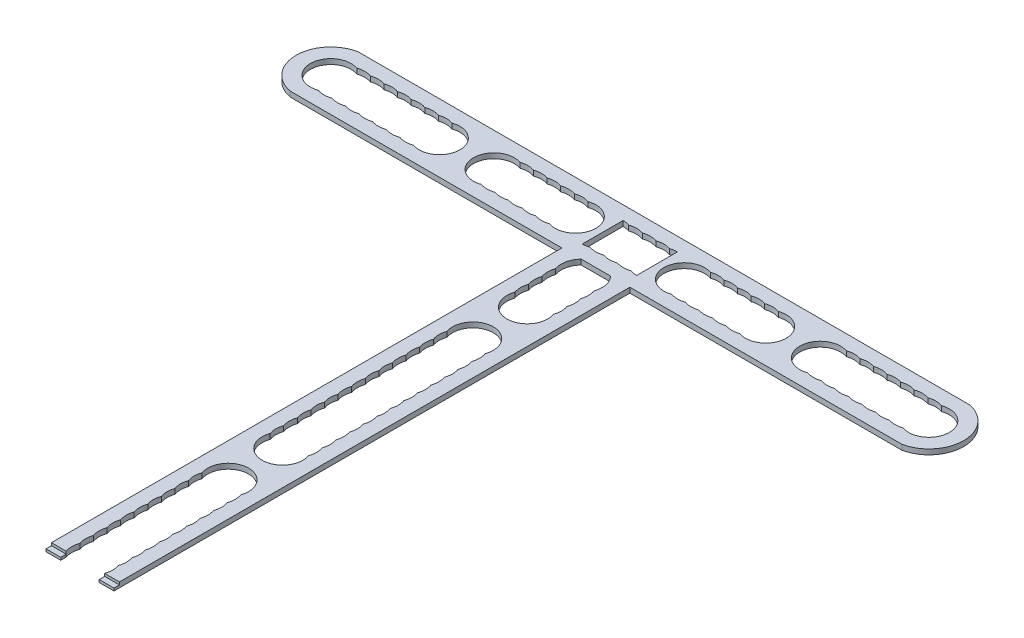
SolidWorks part; units mm, degrees
ref_plane "Front Plane" through (0, 0, 0) normal (0, 0, 1) x (1, 0, 0)
ref_plane "Top Plane" through (0, 0, 0) normal (0, 1, 0) x (1, 0, 0)
ref_plane "Right Plane" through (0, 0, 0) normal (1, 0, 0) x (0, 0, -1)
sketch "Sketch3" plane through (0, 0, 0) normal (0, 1, 0) x (1, 0, 0)
  line L0 (-112.5, 0) -> (112.5, 0) construction
  line L1 (-112.5, -12.5) -> (112.5, -12.5)
  line L2 (-112.5, -12.5) -> (-112.5, 12.5) construction
  line L3 (-112.5, 12.5) -> (112.5, 12.5)
  line L4 (112.5, -12.5) -> (112.5, 12.5) construction
  line L5 (-112.5, -12.5) -> (112.5, 12.5) construction
  line L6 (-112.5, 12.5) -> (112.5, -12.5) construction
  line L7 (60, 12.5) -> (60, -12.5) construction
  line L8 (10, 7.5) -> (10, -7.5)
  line L9 (0, 12.5) -> (0, -12.5) construction
  line L10 (0, 12.5) -> (0, -12.5)
  arc A0 (-2.5, 7.0711) -> (2.5, 7.0711) centre (0, 0) cw
  arc A1 (2.5, 7.0711) -> (7.5, 7.0711) centre (5, 0) cw
  arc A2 (7.5, 7.0711) -> (12.5, 7.0711) centre (10, 0) cw
  arc A3 (12.5, 7.0711) -> (17.5, 7.0711) centre (15, 0) cw
  arc A4 (17.5, 7.0711) -> (22.5, 7.0711) centre (20, 0) cw
  arc A5 (22.5, 7.0711) -> (27.5, 7.0711) centre (25, 0) cw
  arc A6 (27.5, 7.0711) -> (32.5, 7.0711) centre (30, 0) cw
  arc A7 (32.5, 7.0711) -> (37.5, 7.0711) centre (35, 0) cw
  arc A8 (37.5, 7.0711) -> (42.5, 7.0711) centre (40, 0) cw
  arc A9 (42.5, 7.0711) -> (47.5, 7.0711) centre (45, 0) cw
  arc A10 (47.5, 7.0711) -> (52.5, 7.0711) centre (50, 0) cw
  arc A11 (52.5, 7.0711) -> (57.5, 7.0711) centre (55, 0) cw
  arc A12 (57.5, 7.0711) -> (62.5, 7.0711) centre (60, 0) cw
  arc A13 (62.5, 7.0711) -> (67.5, 7.0711) centre (65, 0) cw
  arc A14 (67.5, 7.0711) -> (72.5, 7.0711) centre (70, 0) cw
  arc A15 (72.5, 7.0711) -> (77.5, 7.0711) centre (75, 0) cw
  arc A16 (77.5, 7.0711) -> (82.5, 7.0711) centre (80, 0) cw
  arc A17 (82.5, 7.0711) -> (87.5, 7.0711) centre (85, 0) cw
  arc A18 (87.5, 7.0711) -> (92.5, 7.0711) centre (90, 0) cw
  arc A19 (92.5, 7.0711) -> (97.5, 7.0711) centre (95, 0) cw
  arc A20 (97.5, 7.0711) -> (102.5, 7.0711) centre (100, 0) cw
  arc A21 (102.5, 7.0711) -> (107.5, 7.0711) centre (105, 0) cw
  arc A22 (107.5, 7.0711) -> (112.5, 7.0711) centre (110, 0) cw
  arc A23 (107.5, -7.0711) -> (112.5, -7.0711) centre (110, 0) ccw
  arc A24 (102.5, -7.0711) -> (107.5, -7.0711) centre (105, 0) ccw
  arc A25 (97.5, -7.0711) -> (102.5, -7.0711) centre (100, 0) ccw
  arc A26 (92.5, -7.0711) -> (97.5, -7.0711) centre (95, 0) ccw
  arc A27 (87.5, -7.0711) -> (92.5, -7.0711) centre (90, 0) ccw
  arc A28 (82.5, -7.0711) -> (87.5, -7.0711) centre (85, 0) ccw
  arc A29 (77.5, -7.0711) -> (82.5, -7.0711) centre (80, 0) ccw
  arc A30 (72.5, -7.0711) -> (77.5, -7.0711) centre (75, 0) ccw
  arc A31 (67.5, -7.0711) -> (72.5, -7.0711) centre (70, 0) ccw
  arc A32 (62.5, -7.0711) -> (67.5, -7.0711) centre (65, 0) ccw
  arc A33 (57.5, -7.0711) -> (62.5, -7.0711) centre (60, 0) ccw
  arc A34 (52.5, -7.0711) -> (57.5, -7.0711) centre (55, 0) ccw
  arc A35 (47.5, -7.0711) -> (52.5, -7.0711) centre (50, 0) ccw
  arc A36 (42.5, -7.0711) -> (47.5, -7.0711) centre (45, 0) ccw
  arc A37 (37.5, -7.0711) -> (42.5, -7.0711) centre (40, 0) ccw
  arc A38 (32.5, -7.0711) -> (37.5, -7.0711) centre (35, 0) ccw
  arc A39 (27.5, -7.0711) -> (32.5, -7.0711) centre (30, 0) ccw
  arc A40 (22.5, -7.0711) -> (27.5, -7.0711) centre (25, 0) ccw
  arc A41 (17.5, -7.0711) -> (22.5, -7.0711) centre (20, 0) ccw
  arc A42 (12.5, -7.0711) -> (17.5, -7.0711) centre (15, 0) ccw
  arc A43 (7.5, -7.0711) -> (12.5, -7.0711) centre (10, 0) ccw
  arc A44 (2.5, -7.0711) -> (7.5, -7.0711) centre (5, 0) ccw
  arc A45 (-2.5, -7.0711) -> (2.5, -7.0711) centre (0, 0) ccw
  arc A46 (112.5, 7.0711) -> (112.5, -7.0711) centre (110, 0) cw
  arc A47 (112.5, 12.5) -> (112.5, -12.5) centre (110, 0) cw
  arc A48 (52.5, 7.0711) -> (52.5, -7.0711) centre (50, 0) cw
  arc A49 (67.5, 7.0711) -> (67.5, -7.0711) centre (70, 0) ccw
  arc A50 (17.5, 7.0711) -> (17.5412, -7.0855) centre (20, 0) ccw
  point P0 (0, 0)
  dimension "D4" = 7.5
  dimension "D1" = 225
  dimension "D2" = 25
  dimension "D3" = 5
  dimension "D6" = 60
  dimension "D5" = 23
extrude "Boss-Extrude1" add sketch "Sketch3" along normal blind 1.9 contours A47 L3 L10 A0 A1 A2 A3 A4 A5 A6 A7 A8 A9 A10 A11 A12 A13 A14 A15 A16 A17 A18 A19 A20 A21 A22 A46 A23 A24 A25 A26 A27 A28 A29 A30 A31 A32 A33 A34 A35 A36 A37 A38 A39 A40 A41 A42 A43 | A50 A3 A2 L8 A43 A42 | A49 A13 A12 A11 A48 A34 A33 A32
mirror "Mirror1" about plane through (0, 0, 0) normal (1, 0, 0) of "Boss-Extrude1"
sketch "Sketch4" plane through (0, 0, 0) normal (0, 1, 0) x (1, 0, 0)
  line L0 (-112.5, -12.5) -> (112.5, -12.5) construction
  line L1 (-12.5, -382.9289) -> (12.5, -382.9289)
  line L2 (-12.5, -382.9289) -> (-12.5, -12.5)
  line L3 (-12.5, -12.5) -> (12.5, -12.5)
  line L4 (12.5, -382.9289) -> (12.5, -12.5)
  line L5 (-12.5, -382.9289) -> (12.5, -12.5) construction
  line L6 (-12.5, -12.5) -> (12.5, -382.9289) construction
  line L7 (0, 0) -> (0, -382.9289) construction
  line L8 (-12.5, -200.2145) -> (12.5, -200.2145)
  line L9 (-12.5, -46.875) -> (12.5, -46.875) construction
  line L10 (-12.5, -140.625) -> (12.5, -140.625) construction
  arc A0 (7.0711, -195.2145) -> (7.0711, -200.2145) centre (0, -197.7145) cw
  arc A1 (7.0711, -190.2145) -> (7.0711, -195.2145) centre (0, -192.7145) cw
  arc A2 (7.0711, -185.2145) -> (7.0711, -190.2145) centre (0, -187.7145) cw
  arc A3 (7.0711, -180.2145) -> (7.0711, -185.2145) centre (0, -182.7145) cw
  arc A4 (7.0711, -175.2145) -> (7.0711, -180.2145) centre (0, -177.7145) cw
  arc A5 (7.0711, -170.2145) -> (7.0711, -175.2145) centre (0, -172.7145) cw
  arc A6 (7.0711, -165.2145) -> (7.0711, -170.2145) centre (0, -167.7145) cw
  arc A7 (7.0711, -160.2145) -> (7.0711, -165.2145) centre (0, -162.7145) cw
  arc A8 (7.0711, -155.2145) -> (7.0711, -160.2145) centre (0, -157.7145) cw
  arc A9 (7.0711, -150.2145) -> (7.0711, -155.2145) centre (0, -152.7145) cw
  arc A10 (7.0711, -145.2145) -> (7.0711, -150.2145) centre (0, -147.7145) cw
  arc A11 (7.0711, -140.2145) -> (7.0711, -145.2145) centre (0, -142.7145) cw
  arc A12 (7.0711, -135.2145) -> (7.0711, -140.2145) centre (0, -137.7145) cw
  arc A13 (7.0711, -130.2145) -> (7.0711, -135.2145) centre (0, -132.7145) cw
  arc A14 (7.0711, -125.2145) -> (7.0711, -130.2145) centre (0, -127.7145) cw
  arc A15 (7.0711, -120.2145) -> (7.0711, -125.2145) centre (0, -122.7145) cw
  arc A16 (7.0711, -115.2145) -> (7.0711, -120.2145) centre (0, -117.7145) cw
  arc A17 (7.0711, -110.2145) -> (7.0711, -115.2145) centre (0, -112.7145) cw
  arc A18 (7.0711, -105.2145) -> (7.0711, -110.2145) centre (0, -107.7145) cw
  arc A19 (7.0711, -100.2145) -> (7.0711, -105.2145) centre (0, -102.7145) cw
  arc A20 (7.0711, -95.2145) -> (7.0711, -100.2145) centre (0, -97.7145) cw
  arc A21 (7.0711, -90.2145) -> (7.0711, -95.2145) centre (0, -92.7145) cw
  arc A22 (7.0711, -85.2145) -> (7.0711, -90.2145) centre (0, -87.7145) cw
  arc A23 (7.0711, -80.2145) -> (7.0711, -85.2145) centre (0, -82.7145) cw
  arc A24 (7.0711, -75.2145) -> (7.0711, -80.2145) centre (0, -77.7145) cw
  arc A25 (7.0711, -70.2145) -> (7.0711, -75.2145) centre (0, -72.7145) cw
  arc A26 (7.0711, -65.2145) -> (7.0711, -70.2145) centre (0, -67.7145) cw
  arc A27 (7.0711, -60.2145) -> (7.0711, -65.2145) centre (0, -62.7145) cw
  arc A28 (7.0711, -55.2145) -> (7.0711, -60.2145) centre (0, -57.7145) cw
  arc A29 (7.0711, -50.2145) -> (7.0711, -55.2145) centre (0, -52.7145) cw
  arc A30 (7.0711, -45.2145) -> (7.0711, -50.2145) centre (0, -47.7145) cw
  arc A31 (7.0711, -40.2145) -> (7.0711, -45.2145) centre (0, -42.7145) cw
  arc A32 (7.0711, -35.2145) -> (7.0711, -40.2145) centre (0, -37.7145) cw
  arc A33 (7.0711, -30.2145) -> (7.0711, -35.2145) centre (0, -32.7145) cw
  arc A34 (7.0711, -25.2145) -> (7.0711, -30.2145) centre (0, -27.7145) cw
  arc A35 (7.0711, -20.2145) -> (7.0711, -25.2145) centre (0, -22.7145) cw
  arc A36 (7.0711, -15.2145) -> (7.0711, -20.2145) centre (0, -17.7145) cw
  arc A37 (-7.0711, -195.2145) -> (-7.0711, -200.2145) centre (0, -197.7145) ccw
  arc A38 (-7.0711, -190.2145) -> (-7.0711, -195.2145) centre (0, -192.7145) ccw
  arc A39 (-7.0711, -185.2145) -> (-7.0711, -190.2145) centre (0, -187.7145) ccw
  arc A40 (-7.0711, -180.2145) -> (-7.0711, -185.2145) centre (0, -182.7145) ccw
  arc A41 (-7.0711, -175.2145) -> (-7.0711, -180.2145) centre (0, -177.7145) ccw
  arc A42 (-7.0711, -170.2145) -> (-7.0711, -175.2145) centre (0, -172.7145) ccw
  arc A43 (-7.0711, -165.2145) -> (-7.0711, -170.2145) centre (0, -167.7145) ccw
  arc A44 (-7.0711, -160.2145) -> (-7.0711, -165.2145) centre (0, -162.7145) ccw
  arc A45 (-7.0711, -155.2145) -> (-7.0711, -160.2145) centre (0, -157.7145) ccw
  arc A46 (-7.0711, -150.2145) -> (-7.0711, -155.2145) centre (0, -152.7145) ccw
  arc A47 (-7.0711, -145.2145) -> (-7.0711, -150.2145) centre (0, -147.7145) ccw
  arc A48 (-7.0711, -140.2145) -> (-7.0711, -145.2145) centre (0, -142.7145) ccw
  arc A49 (-7.0711, -135.2145) -> (-7.0711, -140.2145) centre (0, -137.7145) ccw
  arc A50 (-7.0711, -130.2145) -> (-7.0711, -135.2145) centre (0, -132.7145) ccw
  arc A51 (-7.0711, -125.2145) -> (-7.0711, -130.2145) centre (0, -127.7145) ccw
  arc A52 (-7.0711, -120.2145) -> (-7.0711, -125.2145) centre (0, -122.7145) ccw
  arc A53 (-7.0711, -115.2145) -> (-7.0711, -120.2145) centre (0, -117.7145) ccw
  arc A54 (-7.0711, -110.2145) -> (-7.0711, -115.2145) centre (0, -112.7145) ccw
  arc A55 (-7.0711, -105.2145) -> (-7.0711, -110.2145) centre (0, -107.7145) ccw
  arc A56 (-7.0711, -100.2145) -> (-7.0711, -105.2145) centre (0, -102.7145) ccw
  arc A57 (-7.0711, -95.2145) -> (-7.0711, -100.2145) centre (0, -97.7145) ccw
  arc A58 (-7.0711, -90.2145) -> (-7.0711, -95.2145) centre (0, -92.7145) ccw
  arc A59 (-7.0711, -85.2145) -> (-7.0711, -90.2145) centre (0, -87.7145) ccw
  arc A60 (-7.0711, -80.2145) -> (-7.0711, -85.2145) centre (0, -82.7145) ccw
  arc A61 (-7.0711, -75.2145) -> (-7.0711, -80.2145) centre (0, -77.7145) ccw
  arc A62 (-7.0711, -70.2145) -> (-7.0711, -75.2145) centre (0, -72.7145) ccw
  arc A63 (-7.0711, -65.2145) -> (-7.0711, -70.2145) centre (0, -67.7145) ccw
  arc A64 (-7.0711, -60.2145) -> (-7.0711, -65.2145) centre (0, -62.7145) ccw
  arc A65 (-7.0711, -55.2145) -> (-7.0711, -60.2145) centre (0, -57.7145) ccw
  arc A66 (-7.0711, -50.2145) -> (-7.0711, -55.2145) centre (0, -52.7145) ccw
  arc A67 (-7.0711, -45.2145) -> (-7.0711, -50.2145) centre (0, -47.7145) ccw
  arc A68 (-7.0711, -40.2145) -> (-7.0711, -45.2145) centre (0, -42.7145) ccw
  arc A69 (-7.0711, -35.2145) -> (-7.0711, -40.2145) centre (0, -37.7145) ccw
  arc A70 (-7.0711, -30.2145) -> (-7.0711, -35.2145) centre (0, -32.7145) ccw
  arc A71 (-7.0711, -25.2145) -> (-7.0711, -30.2145) centre (0, -27.7145) ccw
  arc A72 (-7.0711, -20.2145) -> (-7.0711, -25.2145) centre (0, -22.7145) ccw
  arc A73 (-7.0711, -15.2145) -> (-7.0711, -20.2145) centre (0, -17.7145) ccw
  arc A74 (7.0711, -15.2145) -> (-7.0711, -15.2145) centre (0, -17.7145) ccw
  arc A75 (-7.0711, -40.2145) -> (7.0711, -40.2145) centre (0, -37.7145) ccw
  arc A76 (7.0711, -55.2145) -> (-7.0711, -55.2145) centre (0, -57.7145) ccw
  arc A77 (-7.0711, -130.2145) -> (7.0711, -130.2145) centre (0, -127.7145) ccw
  arc A78 (7.0711, -145.2145) -> (-7.0711, -145.2145) centre (0, -147.7145) ccw
  point P0 (0, -197.7145)
  dimension "D4" = 7.5
  dimension "D3" = 5
  dimension "D1" = 25
  dimension "D2" = 390
  dimension "D6" = 46.875
  dimension "D7" = 93.75
  dimension "D5" = 37
extrude "Boss-Extrude2" add sketch "Sketch4" along normal blind 1.9 contours A74 A36 A35 A34 A33 A32 A31 A30 A29 A28 A27 A26 A25 A24 A23 A22 A21 A20 A19 A18 A17 A16 A15 A14 A13 A12 A11 A10 A9 A8 A7 A6 A5 A4 A3 A2 A1 A0 L8 L4 L3 | A74 L3 L2 L8 A37 A38 A39 A40 A41 A42 A43 A44 A45 A46 A47 A48 A49 A50 A51 A52 A53 A54 A55 A56 A57 A58 A59 A60 A61 A62 A63 A64 A65 A66 A67 A68 A69 A70 A71 A72 A73 | A76 A29 A30 A31 A75 A68 A67 A66 | A78 A11 A12 A13 A77 A50 A49 A48
sketch "Sketch5" plane through (0, 0, 0) normal (0, 1, 0) x (1, 0, 0)
  line L0 (7.0711, -200.2145) -> (12.5, -200.2145) construction
  line L1 (-12.5, -200.2145) -> (-7.0711, -200.2145)
  line L2 (-12.5, -200.2145) -> (-12.5, -202.2145)
  line L3 (-12.5, -202.2145) -> (-7.0711, -202.2145)
  line L4 (-7.0711, -200.2145) -> (-7.0711, -202.2145)
  line L5 (7.0711, -200.2145) -> (12.5, -200.2145)
  line L6 (7.0711, -200.2145) -> (7.0711, -202.2145)
  line L7 (7.0711, -202.2145) -> (12.5, -202.2145)
  line L8 (12.5, -200.2145) -> (12.5, -202.2145)
  line L9 (12.5, -200.2145) -> (12.5, -12.5) construction
  point P5 (-7.0711, -201.2145)
  dimension "D1" = 2
extrude "Boss-Extrude3" add sketch "Sketch5" along normal blind 0.95
equation "\"diameter_electrode_outer\"= 15mm"
equation "\"width_wing\"= 5mm"
equation "\"rad_curve\"= \"diameter_electrode_outer\" / 2"
equation "\"length_wing\"= 10mm"
equation "\"range_electrode_move_horizontal\"= ( \"length_wing\" / 2 ) * 66"
equation "\"length_slit_horizontal\"= \"diameter_electrode_outer\" + \"range_electrode_move_horizontal\""
equation "\"width_frame\"= \"diameter_electrode_outer\" + \"width_wing\" * 2"
equation "\"height_frame\" = 1.9mm"
equation "\"diameter_fluid_tank_outer\" = 60mm"
equation "\"width_frame_support\"= 10mm"
equation "\"D1@Fillet2\"=\"rad_curve\""
equation "\"range_electrode_move_vertical\" = ( \"length_wing\" / 2 ) * 75"
equation "\"length_slit_vertical\"= \"diameter_electrode_outer\" + \"range_electrode_move_vertical\""
equation "\"circumference_head\"= 600mm"
equation "\"range_electrode_move_front\" = \"circumference_head\" * 3.5 / 10"
equation "\"length_slit_front\"= \"range_electrode_move_front\" + \"diameter_electrode_outer\""
equation "\"D1@Sketch3\"=\"length_slit_front\""
equation "\"D2@Sketch3\"=\"diameter_electrode_outer\"+2*\"width_wing\""
equation "\"D3@Sketch3\"=\"length_wing\"/2"
equation "\"D4@Sketch3\"=\"rad_curve\""
equation "\"D6@Sketch3\"=\"circumference_head\"/10"
equation "\"D1@Boss-Extrude1\"=\"height_frame\""
equation "\"D1@Sketch4\"=\"diameter_electrode_outer\"+2*\"width_wing\""
equation "\"D2@Sketch4\"=\"length_slit_vertical\""
equation "\"D3@Sketch4\"=\"length_wing\"/2"
equation "\"D4@Sketch4\"=\"rad_curve\""
equation "\"D6@Sketch4\"=\"range_electrode_move_vertical\"*0.5/4"
equation "\"D7@Sketch4\"=\"range_electrode_move_vertical\"/4"
equation "\"D1@Boss-Extrude2\"=\"height_frame\""
equation "\"D1@Sketch5\"=\"width_connect\""
equation "\"width_connect\"= 2mm"
equation "\"height_connect\"= \"height_frame\" / 2"
equation "\"D1@Boss-Extrude3\"=\"height_connect\""
equation "\"length_slit_vertical\"= \"range_electrode_move_vertical\" + \"diameter_electrode_outer\""
